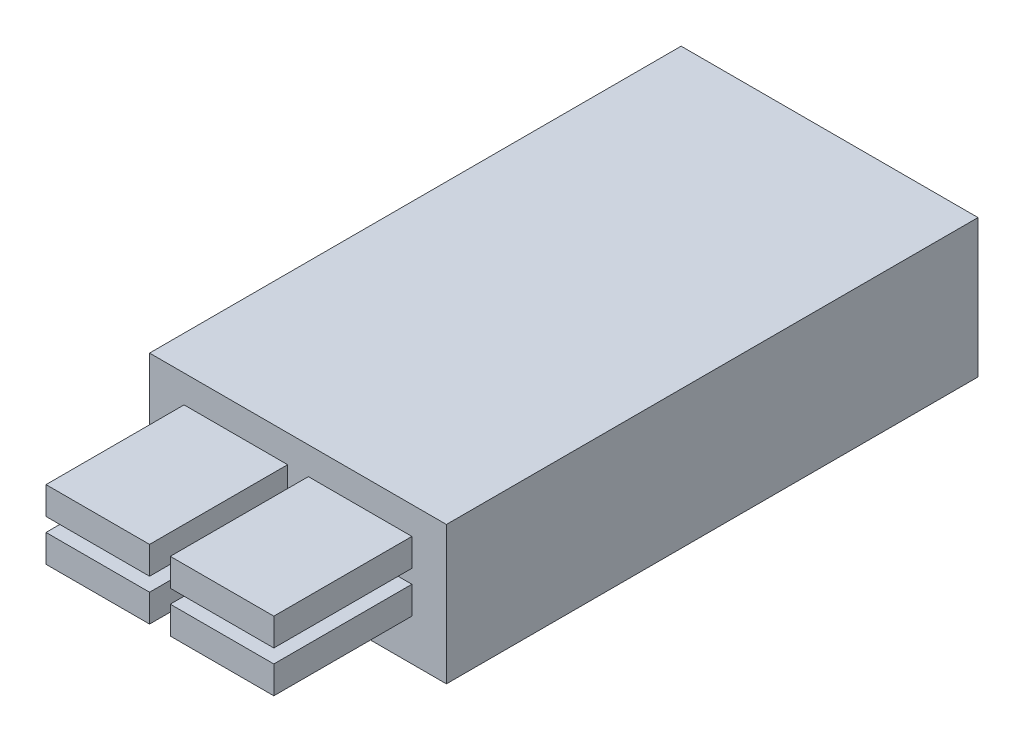
SolidWorks part; units mm, degrees
ref_plane "Front" through (0, 0, 0) normal (0, 0, 1) x (1, 0, 0)
ref_plane "Top" through (0, 0, 0) normal (0, 1, 0) x (1, 0, 0)
ref_plane "Right" through (0, 0, 0) normal (1, 0, 0) x (0, 0, -1)
sketch "Sketch1" plane through (0, 0, 0) normal (0, 1, 0) x (1, 0, 0)
  line L1 (-10.75, 19.25) -> (10.75, 19.25)
  line L2 (-10.75, 19.25) -> (-10.75, -19.25)
  line L3 (-10.75, -19.25) -> (10.75, -19.25)
  line L4 (10.75, 19.25) -> (10.75, -19.25)
  line L5 (-10.75, 19.25) -> (10.75, -19.25) construction
  line L6 (-10.75, -19.25) -> (10.75, 19.25) construction
  point P0 (0, 0)
  dimension "D1" = 21.5
  dimension "D2" = 38.5
extrude "Boss-Extrude1" add sketch "Sketch1" along normal blind 10
sketch "Sketch2" plane through (0, 0, 19.25) normal (0, 0, 1) x (1, 0, 0)
  line L0 (-10.75, 7) -> (10.75, 7) construction
  line L1 (-10.75, 10) -> (-10.75, 0) construction
  line L2 (10.75, 10) -> (10.75, 0) construction
  line L3 (-10.75, 4) -> (10.75, 4) construction
  line L4 (-10.75, 10) -> (10.75, 10) construction
  line L5 (0, 10) -> (0, 0) construction
  line L6 (-8.25, 8) -> (-0.75, 8)
  line L7 (-8.25, 8) -> (-8.25, 6)
  line L8 (-8.25, 6) -> (-0.75, 6)
  line L9 (-0.75, 8) -> (-0.75, 6)
  line L10 (-8.25, 8) -> (-0.75, 6) construction
  line L11 (-8.25, 6) -> (-0.75, 8) construction
  line L12 (0.75, 5) -> (0.75, 3)
  line L13 (-8.25, 5) -> (-0.75, 5)
  line L14 (-8.25, 5) -> (-8.25, 3)
  line L15 (-8.25, 3) -> (-0.75, 3)
  line L16 (-0.75, 5) -> (-0.75, 3)
  line L17 (-8.25, 5) -> (-0.75, 3) construction
  line L18 (-8.25, 3) -> (-0.75, 5) construction
  line L19 (8.25, 3) -> (0.75, 3)
  line L20 (8.25, 5) -> (0.75, 5)
  line L21 (8.25, 5) -> (8.25, 3)
  line L22 (8.25, 8) -> (8.25, 6)
  line L23 (0.75, 8) -> (0.75, 6)
  line L24 (8.25, 6) -> (0.75, 6)
  line L25 (8.25, 8) -> (0.75, 8)
  point P10 (-4.5, 7)
  point P18 (-4.5, 4)
  dimension "D1" = 3
  dimension "D2" = 6
  dimension "D3" = 4.5
  dimension "D4" = 7.5
  dimension "D5" = 7.5
  dimension "D6" = 2
  dimension "D7" = 2
extrude "Boss-Extrude2" add sketch "Sketch2" along normal blind 10
